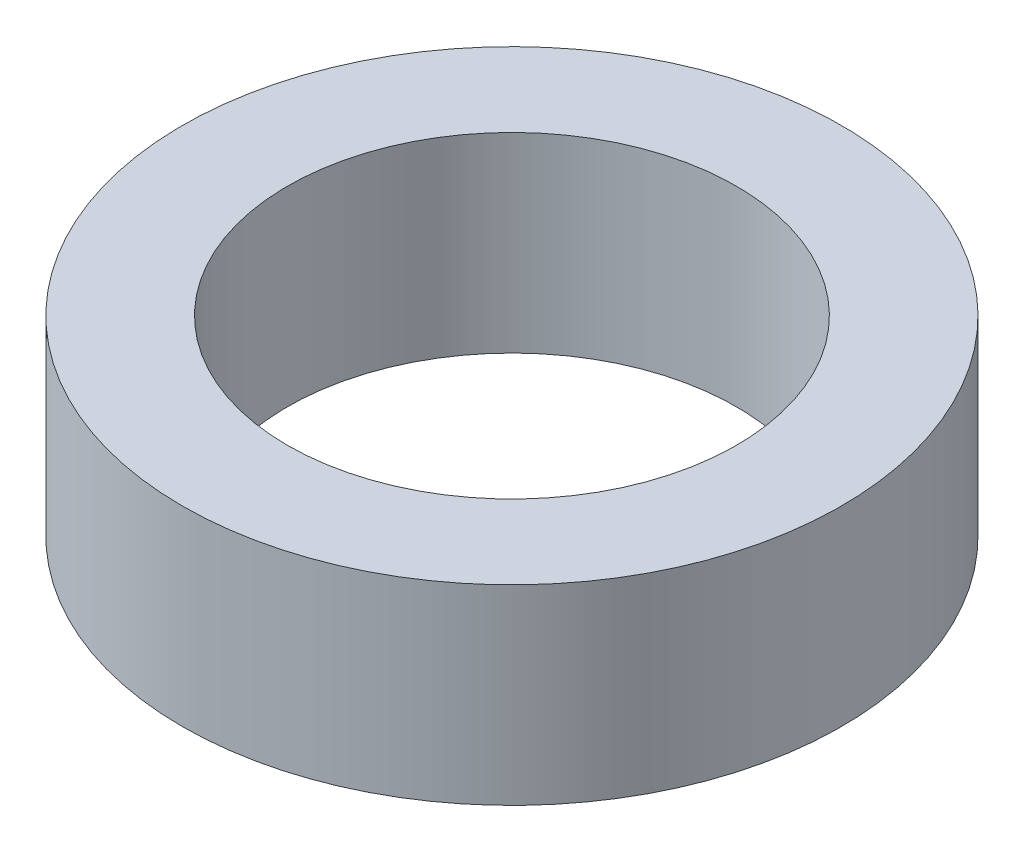
SolidWorks part; units mm, degrees
material "Cast Alloy Steel"
ref_plane "Front Plane" through (0, 0, 0) normal (0, 0, 1) x (1, 0, 0)
ref_plane "Top Plane" through (0, 0, 0) normal (0, 1, 0) x (1, 0, 0)
ref_plane "Right Plane" through (0, 0, 0) normal (1, 0, 0) x (0, 0, -1)
sketch "Sketch1" plane through (0, 0, 0) normal (0, 1, 0) x (1, 0, 0)
  circle A0 centre (0, 0) radius 1.725
  circle A1 centre (0, 0) radius 1.175
  dimension "D1" = 3.45
  dimension "D2" = 2.35
extrude "Boss-Extrude1" add sketch "Sketch1" along normal blind 1
